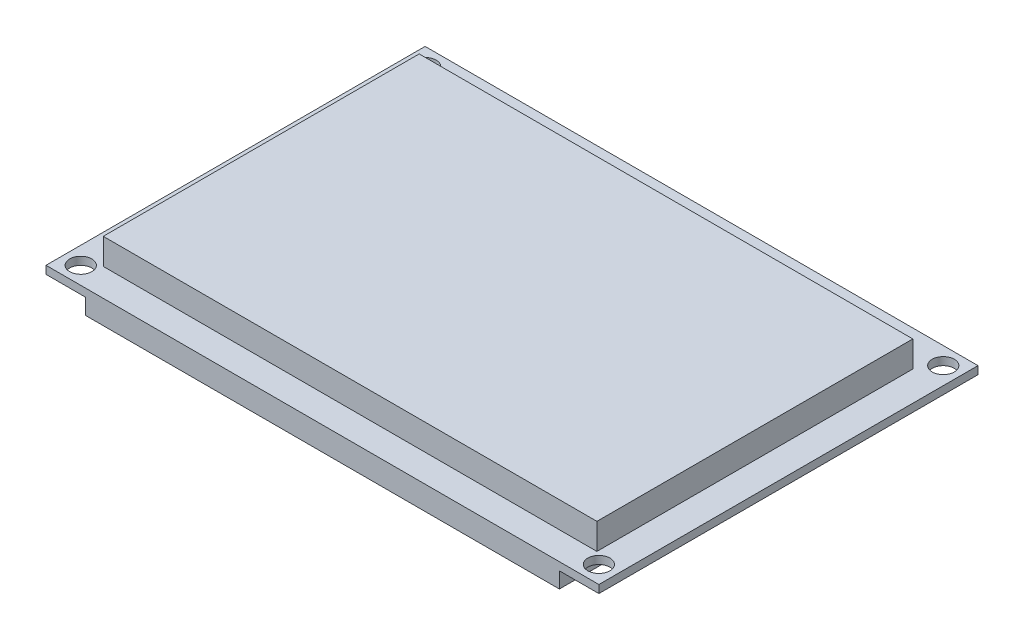
SolidWorks part; units mm, degrees
ref_plane "Front Plane" through (0, 0, 0) normal (0, 0, 1) x (1, 0, 0)
ref_plane "Top Plane" through (0, 0, 0) normal (0, 1, 0) x (1, 0, 0)
ref_plane "Right Plane" through (0, 0, 0) normal (1, 0, 0) x (0, 0, -1)
sketch "Sketch1" plane through (0, 0, 0) normal (0, 1, 0) x (1, 0, 0)
  line L0 (-2.2, 45.8) -> (-2.2, 48) construction
  line L1 (0, 0) -> (-70, 0)
  line L2 (0, 0) -> (0, 48)
  line L3 (0, 48) -> (-70, 48)
  line L4 (-70, 0) -> (-70, 48)
  line L5 (-66.25, 43.5) -> (-3.75, 43.5) construction
  line L6 (-66.25, 43.5) -> (-66.25, 3.5) construction
  line L7 (-66.25, 3.5) -> (-3.75, 3.5) construction
  line L8 (-3.75, 43.5) -> (-3.75, 3.5) construction
  line L9 (-67.8, 2.2) -> (-67.8, 0) construction
  line L10 (0, 45.8) -> (-2.2, 45.8) construction
  line L11 (-38.6, 45.2) -> (-36.2, 45.2) construction
  line L12 (-70, 2.2) -> (-67.8, 2.2) construction
  line L13 (-36.2, 45.2) -> (-33.8, 45.2) construction
  line L14 (-33.8, 45.2) -> (-31.4, 45.2) construction
  line L15 (-68.2, 27.6) -> (-68.2, 25.2) construction
  line L16 (-68.2, 25.2) -> (-68.2, 22.8) construction
  line L17 (-68.2, 22.8) -> (-68.2, 20.4) construction
  line L19 (-65, 43) -> (-5, 43) construction
  line L20 (-65, 43) -> (-65, 0) construction
  line L21 (-65, 0) -> (-5, 0)
  line L22 (-5, 43) -> (-5, 0) construction
  circle A0 centre (-2.2, 45.8) radius 1.4
  circle A1 centre (-2.2, 2.2) radius 1.4
  circle A2 centre (-67.8, 2.2) radius 1.4
  circle A3 centre (-67.8, 45.8) radius 1.4
  circle A4 centre (-38.6, 45.2) radius 0.5
  circle A5 centre (-36.2, 45.2) radius 0.5
  circle A6 centre (-33.8, 45.2) radius 0.5
  circle A7 centre (-31.4, 45.2) radius 0.5
  circle A8 centre (-68.2, 27.6) radius 0.5
  circle A9 centre (-68.2, 25.2) radius 0.5
  circle A10 centre (-68.2, 22.8) radius 0.5
  circle A11 centre (-68.2, 20.4) radius 0.5
  point P9 (-35, 43.5)
  point P10 (-35, 48)
  point P31 (-35, 45.2)
  point P40 (-68.2, 24)
  point P41 (-70, 24)
  dimension "D6" = 2.8
  dimension "D8" = 1
  dimension "D1" = 48
  dimension "D2" = 70
  dimension "D3" = 40
  dimension "D4" = 62.5
  dimension "D5" = 4.5
  dimension "D7" = 2.2
  dimension "D9" = 2.8
  dimension "D10" = 7.2
  dimension "D11" = 7.2
  dimension "D12" = 1.8
  dimension "D13" = 5
  dimension "D14" = 5
  dimension "D15" = 5
extrude "Boss-Extrude1" add sketch "Sketch1" along normal blind 1 contours L4 L1 L2 L3 A11 A10 A9 A8 A7 A6 A5 A4 A3 A2 A1 A0
sketch "Sketch2" plane through (0, 1, 0) normal (0, 1, 0) x (1, 0, 0)
  line L1 (-66.25, 43.5) -> (-3.75, 43.5)
  line L2 (-66.25, 43.5) -> (-66.25, 3.5)
  line L3 (-66.25, 3.5) -> (-3.75, 3.5)
  line L4 (-3.75, 43.5) -> (-3.75, 3.5)
extrude "Boss-Extrude2" add sketch "Sketch2" along normal blind 3.3
sketch "Sketch3" plane through (0, 0, 0) normal (0, -1, 0) x (1, 0, 0)
  line L1 (-65, -43) -> (-5, -43)
  line L2 (-65, -43) -> (-65, 0)
  line L3 (-65, 0) -> (-5, 0)
  line L4 (-5, -43) -> (-5, 0)
extrude "Boss-Extrude3" add sketch "Sketch3" along normal blind 2
